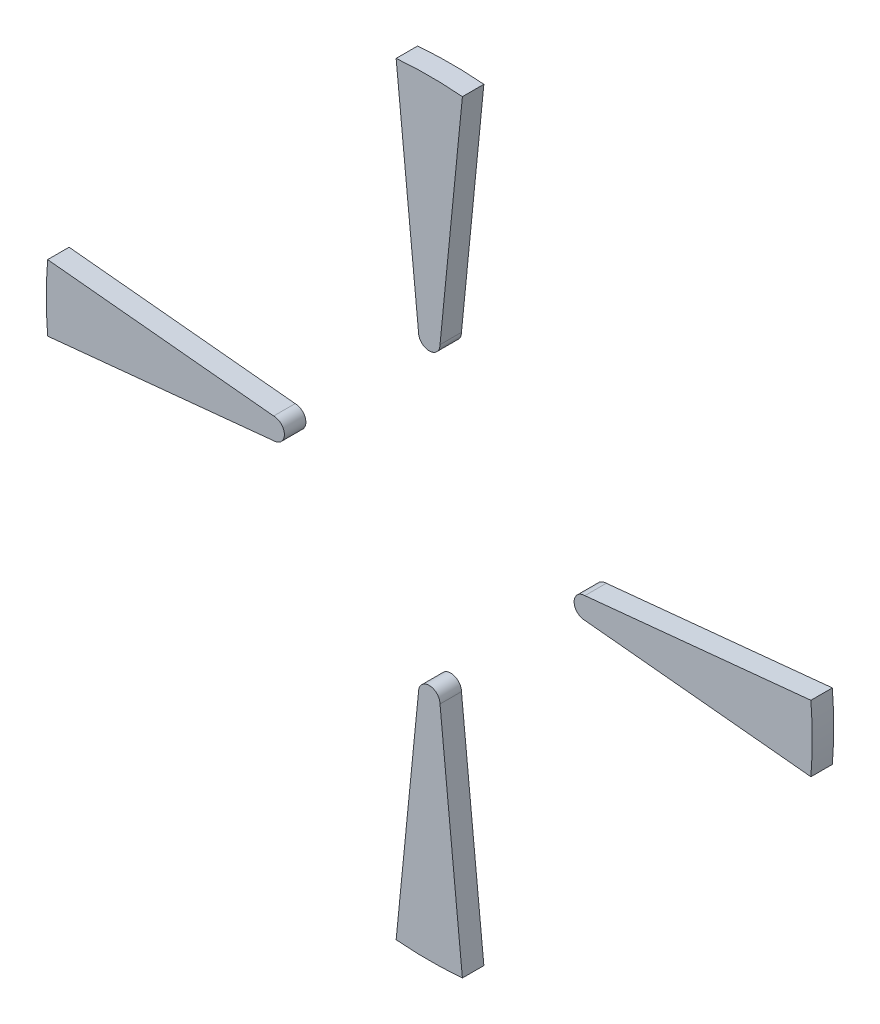
SolidWorks part; units mm, degrees
ref_plane "前基準面" through (0, 0, 0) normal (0, 0, 1) x (1, 0, 0)
ref_plane "上基準面" through (0, 0, 0) normal (0, 1, 0) x (1, 0, 0)
ref_plane "右基準面" through (0, 0, 0) normal (1, 0, 0) x (0, 0, -1)
sketch "草圖1" plane through (0, 0, 0) normal (0, 0, 1) x (1, 0, 0)
  line L0 (0, 0) -> (0, 1.6116) construction
  line L1 (-0.03, 0.435) -> (-0.0926, 1.067)
  line L2 (0.03, 0.435) -> (0.0926, 1.067)
  line L3 (0.435, 0.03) -> (1.067, 0.0926)
  line L4 (0.435, -0.03) -> (1.067, -0.0926)
  line L5 (0.03, -0.435) -> (0.0926, -1.067)
  line L6 (-0.03, -0.435) -> (-0.0926, -1.067)
  line L7 (-0.435, -0.03) -> (-1.067, -0.0926)
  line L8 (-0.435, 0.03) -> (-1.067, 0.0926)
  circle A0 centre (0, 0) radius 0.405
  arc A1 (0.0926, 1.067) -> (-0.0926, 1.067) centre (0, 0) ccw
  arc A2 (-0.03, 0.435) -> (0.03, 0.435) centre (0, 0.435) ccw
  arc A3 (1.067, -0.0926) -> (1.067, 0.0926) centre (0, 0) ccw
  arc A4 (0.435, 0.03) -> (0.435, -0.03) centre (0.435, 0) ccw
  arc A5 (-0.0926, -1.067) -> (0.0926, -1.067) centre (0, 0) ccw
  arc A6 (0.03, -0.435) -> (-0.03, -0.435) centre (0, -0.435) ccw
  arc A7 (-1.067, 0.0926) -> (-1.067, -0.0926) centre (0, 0) ccw
  arc A8 (-0.435, -0.03) -> (-0.435, 0.03) centre (-0.435, 0) ccw
  point P27 (0, 0)
  dimension "D1" = 5.66
  dimension "D2" = 4
extrude "填料-伸長1" add sketch "草圖1" along normal blind 0.06 contours A2 L0 A1 L1 | L0 A2 L2 A1 | A8 L8 A7 L7 | L5 A6 L6 A5 | L3 A4 L4 A3
